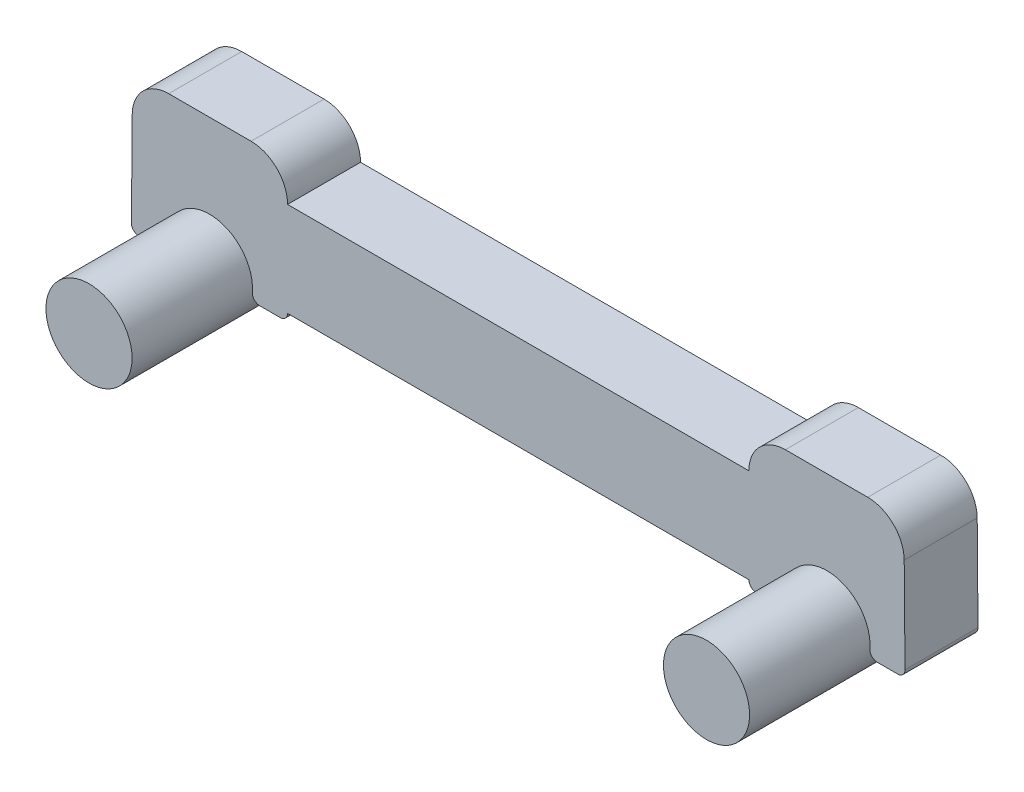
SolidWorks part; units mm, degrees
ref_plane "Front Plane" through (0, 0, 0) normal (0, 0, 1) x (1, 0, 0)
ref_plane "Top Plane" through (0, 0, 0) normal (0, 1, 0) x (1, 0, 0)
ref_plane "Right Plane" through (0, 0, 0) normal (1, 0, 0) x (0, 0, -1)
sketch "Sketch1" plane through (0, 0, 0) normal (0, 0, 1) x (1, 0, 0)
  circle A0 centre (0, 0) radius 1.4986
  dimension "D1" = 2.9972
extrude "Boss-Extrude1" add sketch "Sketch1" along normal blind 6.731
sketch "Sketch2" plane through (0, 0, 0) normal (0, 0, -1) x (-1, 0, 0)
  line L2 (0, 0) -> (0, -1.6094) construction
  line L14 (0, 1.2446) -> (-1.6929, 1.2446) construction
  line L15 (0, 1.2446) -> (1.6929, 1.2446) construction
  line L27 (-1.7475, -0.3879) -> (-2.4635, -0.3879)
  line L28 (1.7475, -0.3879) -> (2.4614, -0.3879)
  line L29 (-2.7175, 3.1496) -> (-2.7175, -0.1339)
  line L30 (2.7154, -0.1317) -> (2.6879, 3.1602)
  line L31 (-1.4475, 4.4196) -> (1.4179, 4.4196)
  arc A12 (-1.4942, -0.1145) -> (1.4942, -0.1145) centre (0, 0) cw
  arc A15 (-2.7175, 3.1496) -> (-1.4475, 4.4196) centre (-1.4475, 3.1496) cw
  arc A16 (1.4179, 4.4196) -> (2.6879, 3.1602) centre (1.4179, 3.1496) cw
  arc A17 (2.4614, -0.3879) -> (2.7154, -0.1317) centre (2.4614, -0.1339) ccw
  arc A18 (1.7475, -0.3879) -> (1.4942, -0.1145) centre (1.7475, -0.1339) cw
  arc A19 (-2.4635, -0.3879) -> (-2.7175, -0.1339) centre (-2.4635, -0.1339) cw
  arc A20 (-1.7475, -0.3879) -> (-1.4942, -0.1145) centre (-1.7475, -0.1339) ccw
  point P16 (1.2022, -0.3221)
  point P24 (0, 1.2446)
  dimension "D2" = 1.27
  dimension "D1" = 0.254
  dimension "D3" = 1.27
extrude "Boss-Extrude2" add sketch "Sketch2" against normal blind 2.54
sketch "Sketch3" plane through (2.7175, 0, 0) normal (1, 0, 0) x (0, 0, -1)
  line L1 (0, -0.1339) -> (-2.54, -0.1339)
  line L2 (0, -0.1339) -> (0, 3.1496)
  line L3 (0, 3.1496) -> (-2.54, 3.1496)
  line L4 (-2.54, -0.1339) -> (-2.54, 3.1496)
extrude "Boss-Extrude3" add sketch "Sketch3" along normal blind 8.0264
mirror "Mirror4" about plane through (10.7439, 0, 0) normal (1, 0, 0) of bodies 103
